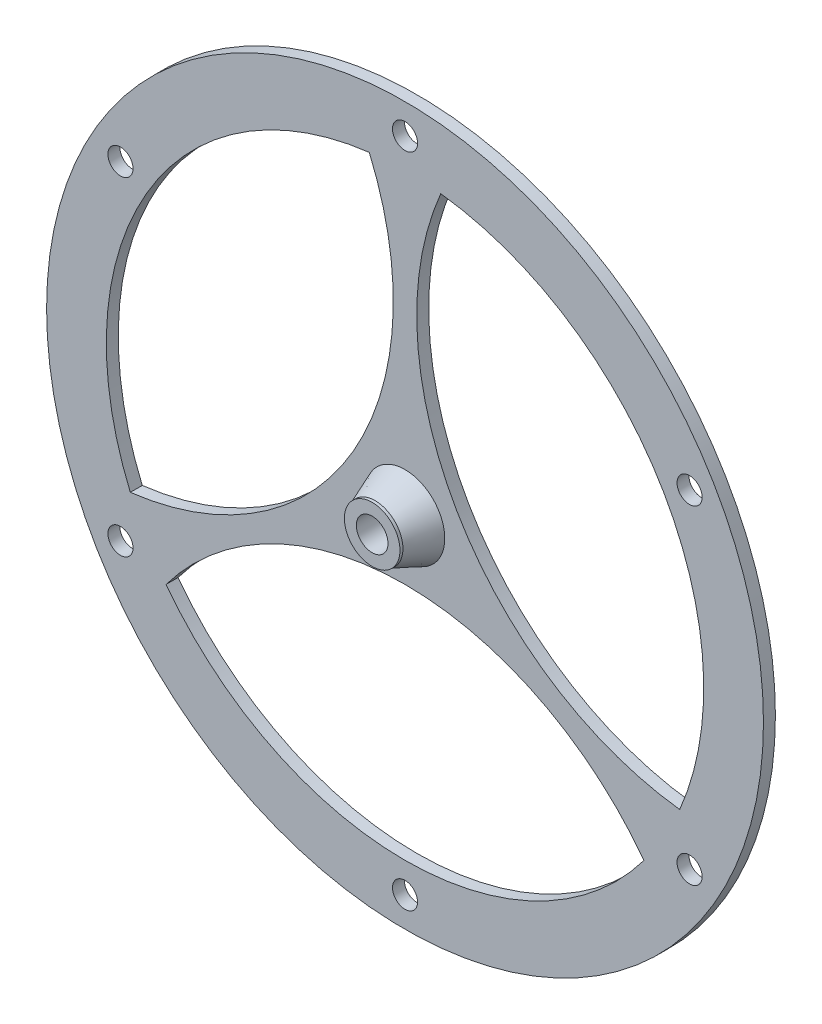
SolidWorks part; units mm, degrees
material "ABS PC"
ref_plane "Front Plane" through (0, 0, 0) normal (0, 0, 1) x (1, 0, 0)
ref_plane "Top Plane" through (0, 0, 0) normal (0, 1, 0) x (1, 0, 0)
ref_plane "Right Plane" through (0, 0, 0) normal (1, 0, 0) x (0, 0, -1)
sketch "Sketch1" plane through (0, 0, 0) normal (0, 0, 1) x (1, 0, 0)
  line L0 (0, 0) -> (0, -60) construction
  line L1 (0, 0) -> (51.9615, 30) construction
  line L2 (0, 0) -> (-51.9615, 30) construction
  circle A0 centre (0, 0) radius 50
  circle A1 centre (0, 0) radius 10
  circle A2 centre (0, 0) radius 60
  circle A3 centre (-51.9615, 30) radius 50
  circle A4 centre (51.9615, 30) radius 50
  circle A5 centre (0, -60) radius 50
  circle A6 centre (0, 0) radius 2.65
  dimension "D1" = 100
  dimension "D2" = 20
  dimension "D6" = 5.3
  dimension "D4" = 120
  dimension "D5" = 120
  dimension "D3" = 10
extrude "Boss-Extrude2" add sketch "Sketch1" along normal blind 2 contours A5 A0 A4 A1 | A1 A6 | A4 A0 A3 A1 | A5 A1 A3 A0 | A4 A2 A3 A0 | A2 A4 A0 | A5 A2 A4 A0 | A2 A5 A0 | A5 A0 A3 A2 | A0 A3 A2
sketch "Sketch2" plane through (0, 0, 2) normal (0, 0, 1) x (1, 0, 0)
  line L0 (0, 0) -> (0, 85.8559)
  circle A0 centre (0, 55) radius 2.1
  circle A1 centre (0, 0) radius 2.65 construction
  dimension "D2" = 4.2
  dimension "D1" = 55
extrude "Cut-Extrude1" cut sketch "Sketch2" against normal through all contours L0 A0 | L0 A0
pattern_circular "CirPattern1" count 6 over 360 about axis through (0, 0, 0) along (0, 0, 1) of "Cut-Extrude1"
sketch "Sketch3" plane through (0, 0, 2) normal (0, 0, 1) x (1, 0, 0)
  circle A1 centre (0, 0) radius 2.65
  circle A4 centre (0, 0) radius 4.65
  circle A5 centre (0, 0) radius 4.65
  dimension "D2" = 5.3
  dimension "D1" = 2
extrude "Boss-Extrude3" add sketch "Sketch3" along normal blind 5.5
chamfer "Chamfer1" distance 2 distance2 5 1 edges at (4.65, 0, 2)
equation "\"wheelDiam\"= 10cm"
equation "\"m5Clearance\"= 5.3mm"
equation "\"motorDiam\"= 20mm"
equation "\"D1@Sketch1\"=\"wheelDiam\""
equation "\"D6@Sketch1\"=\"m5Clearance\""
equation "\"D2@Sketch1\"=\"motorDiam\""
equation "\"D1@Sketch2\"=\"wheelDiam\"/2+0.005"
equation "\"D2@Sketch3\"=\"m5Clearance\""
